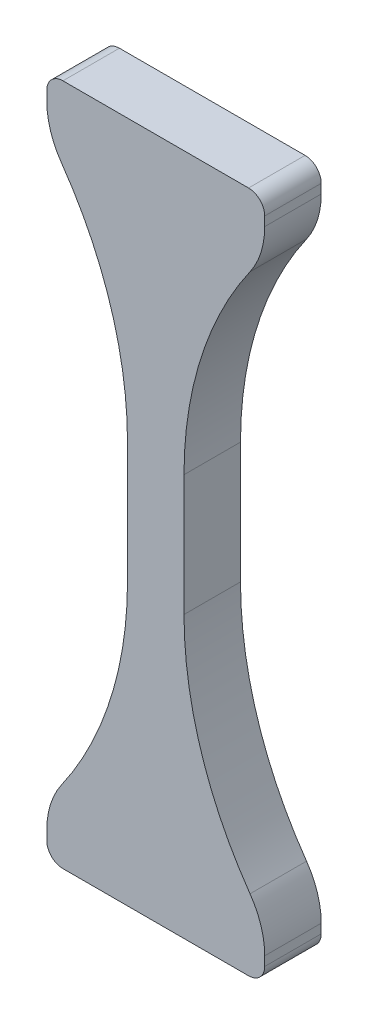
SolidWorks part; units mm, degrees
ref_plane "Front Plane" through (0, 0, 0) normal (0, 0, 1) x (1, 0, 0)
ref_plane "Top Plane" through (0, 0, 0) normal (0, 1, 0) x (1, 0, 0)
ref_plane "Right Plane" through (0, 0, 0) normal (1, 0, 0) x (0, 0, -1)
sketch "Sketch1" plane through (0, 0, 0) normal (0, 0, 1) x (1, 0, 0)
  line L5 (-13.5, -1.5201) -> (-13.5, -0.3772)
  line L6 (-11.5, 1.6228) -> (11.5, 1.6228)
  line L7 (13.5, -0.3772) -> (13.5, -1.5201)
  line L13 (3.5, -33.1429) -> (3.5, -40.6429)
  line L14 (3.5, -40.6429) -> (-3.5, -40.6429)
  line L15 (-3.5, -40.6429) -> (-3.5, -33.1429)
  line L22 (-3.5, -33.1429) -> (3.5, -33.1429) construction
  line L23 (-11.6818, -7.2697) -> (11.6818, -7.2697) construction
  line L24 (0, 3.6228) -> (0, -7.2697) construction
  line L25 (12.7, 3.6228) -> (-12.7, 3.6228) construction
  arc A2 (11.7818, -7.1268) -> (3.7267, -29.625) centre (48.6, -33) ccw construction
  arc A3 (11.7818, -7.1268) -> (3.7267, -29.625) centre (48.6, -33) ccw construction
  arc A24 (13.5, -1.5201) -> (11.6818, -7.2697) centre (3.5, -1.5201) cw
  arc A25 (-13.5, -1.5201) -> (-11.6818, -7.2697) centre (-3.5, -1.5201) ccw
  arc A26 (-11.6818, -7.2697) -> (-3.5, -33.1429) centre (-48.5, -33.1429) cw
  arc A27 (11.6818, -7.2697) -> (3.5, -33.1429) centre (48.5, -33.1429) ccw
  arc A28 (11.5, 1.6228) -> (13.5, -0.3772) centre (11.5, -0.3772) cw
  arc A29 (-13.5, -0.3772) -> (-11.5, 1.6228) centre (-11.5, -0.3772) cw
  dimension "D1" = 10
  dimension "D2" = 45
  dimension "D4" = 2
  dimension "7" = 7
  dimension "D3" = 27
  dimension "D5" = 2
  dimension "D6" = 7.5
extrude "Boss-Extrude1" add sketch "Sketch1" along normal blind 7
mirror "Mirror1" about plane through (3.5, -40.6429, 7) normal (0, 1, 0) of "Boss-Extrude1"
